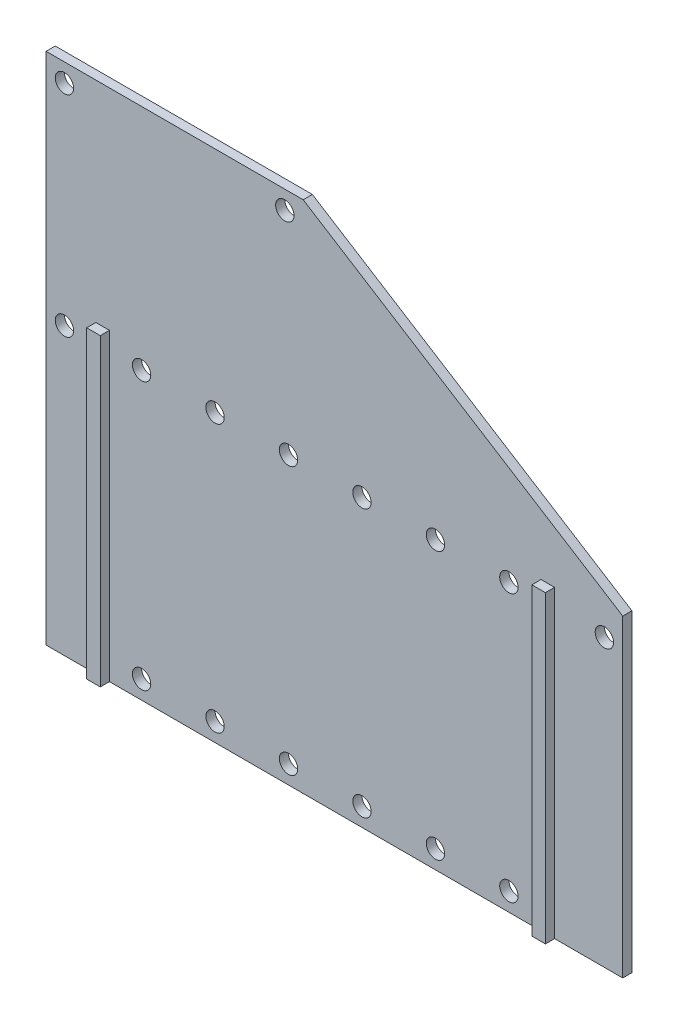
SolidWorks part; units mm, degrees
material "6061-T6 (SS)"
ref_plane "Front Plane" through (0, 0, 0) normal (0, 0, 1) x (1, 0, 0)
ref_plane "Top Plane" through (0, 0, 0) normal (0, 1, 0) x (1, 0, 0)
ref_plane "Right Plane" through (0, 0, 0) normal (1, 0, 0) x (0, 0, -1)
sketch "Sketch1" plane through (0, 0, 0) normal (0, 0, 1) x (1, 0, 0)
  line L1 (-99.695, -88.9) -> (99.695, -88.9)
  line L2 (-99.695, -88.9) -> (-99.695, 88.9)
  line L3 (-99.695, 88.9) -> (99.695, 88.9)
  line L4 (99.695, -88.9) -> (99.695, 88.9)
  line L5 (-99.695, -88.9) -> (99.695, 88.9) construction
  line L6 (-99.695, 88.9) -> (99.695, -88.9) construction
  point P0 (0, 0)
  dimension "D1" = 177.8
  dimension "D2" = 199.39
extrude "Boss-Extrude1" add sketch "Sketch1" along normal blind 3.175 contours L3 L4 L1 L2
sketch "Sketch6" plane through (0, 0, 3.175) normal (0, 0, 1) x (1, 0, 0)
  line L0 (0, 88.9) -> (0, 19.475) construction
  line L1 (-99.695, 88.9) -> (99.695, 88.9) construction
  line L2 (-99.695, 88.9) -> (-10.795, 88.9) construction
  line L11 (99.695, 88.9) -> (99.695, 19.475)
  line L13 (-10.795, 88.9) -> (99.695, 19.475)
  line L14 (0, 19.475) -> (99.695, 19.475) construction
  line L16 (99.695, 88.9) -> (-10.795, 88.9)
  line L18 (99.695, -88.9) -> (99.695, 88.9) construction
  dimension "D1" = 69.425
  dimension "D2" = 88.9
  dimension "D3" = 0
  dimension "D5" = 69.425
extrude "Cut-Extrude4" cut sketch "Sketch6" against normal through all
sketch "Sketch7" plane through (0, 0, 3.175) normal (0, 0, 1) x (1, 0, 0)
  line L0 (-99.695, -88.9) -> (99.695, -88.9) construction
  line L1 (-99.695, -88.9) -> (-99.695, 88.9) construction
  line L2 (99.695, -88.9) -> (99.695, 19.475) construction
  line L3 (-99.695, 88.9) -> (-10.795, 88.9) construction
  line L4 (-66.675, -88.9) -> (-66.675, 9.95) construction
  line L5 (-93.345, 82.55) -> (-17.145, 82.55) construction
  circle A2 centre (-93.345, 82.55) radius 3.175
  circle A3 centre (-93.345, 9.95) radius 3.175
  circle A4 centre (93.345, 9.95) radius 3.175
  circle A5 centre (-66.675, 9.95) radius 3.175
  circle A6 centre (-41.275, 9.95) radius 3.175
  circle A7 centre (-15.875, 9.95) radius 3.175
  circle A8 centre (9.525, 9.95) radius 3.175
  circle A9 centre (34.925, 9.95) radius 3.175
  circle A10 centre (60.325, 9.95) radius 3.175
  circle A11 centre (-17.145, 82.55) radius 3.175
  circle A13 centre (-66.675, -82.55) radius 3.175
  circle A14 centre (-41.275, -82.55) radius 3.175
  circle A15 centre (-15.875, -82.55) radius 3.175
  circle A16 centre (9.525, -82.55) radius 3.175
  circle A17 centre (34.925, -82.55) radius 3.175
  circle A18 centre (60.325, -82.55) radius 3.175
  dimension "D4" = 6
  dimension "D6" = 6.35
  dimension "D9" = 6.35
  dimension "D10" = 6.35
  dimension "D12" = 6
  dimension "D14" = 6.35
  dimension "D16" = 6.35
  dimension "D2" = 6.35
  dimension "D3" = 6.35
  dimension "D5" = 6.35
  dimension "D7" = 6.35
  dimension "D8" = 98.85
  dimension "D11" = 33.02
  dimension "D13" = 98.85
  dimension "3.82923228" = 98.85
  dimension "D15" = 6.35
  dimension "D17" = 6.35
extrude "Cut-Extrude5" cut sketch "Sketch7" against normal through all
sketch "Sketch8" plane through (0, 0, 3.175) normal (0, 0, 1) x (1, 0, 0)
  line L0 (-99.695, -88.9) -> (99.695, -88.9) construction
  line L2 (-77.7875, 16.3) -> (-77.7875, -88.9)
  line L4 (71.4375, 16.3) -> (71.4375, -88.9)
  line L5 (-66.675, -82.55) -> (60.325, -82.55) construction
  line L6 (-66.675, 9.95) -> (60.325, 9.95) construction
  line L7 (-3.175, -82.55) -> (-3.175, -88.9) construction
  line L8 (-82.4865, -88.9) -> (-82.4865, 16.3)
  line L9 (71.4375, 16.3) -> (76.1365, 16.3)
  line L10 (76.1365, 16.3) -> (76.1365, -88.9)
  line L11 (71.4375, -88.9) -> (76.1365, -88.9)
  line L12 (-82.4865, 16.3) -> (-77.7875, 16.3)
  line L13 (-82.4865, -88.9) -> (-77.7875, -88.9)
  line L14 (-77.7875, -36.3) -> (71.4375, -36.3) construction
  point P22 (-3.175, -36.3)
  dimension "D1" = 4.699
  dimension "D2" = 4.699
  dimension "D3" = 149.225
  dimension "D4" = 0
extrude "Boss-Extrude2" add sketch "Sketch8" along normal blind 3.175
